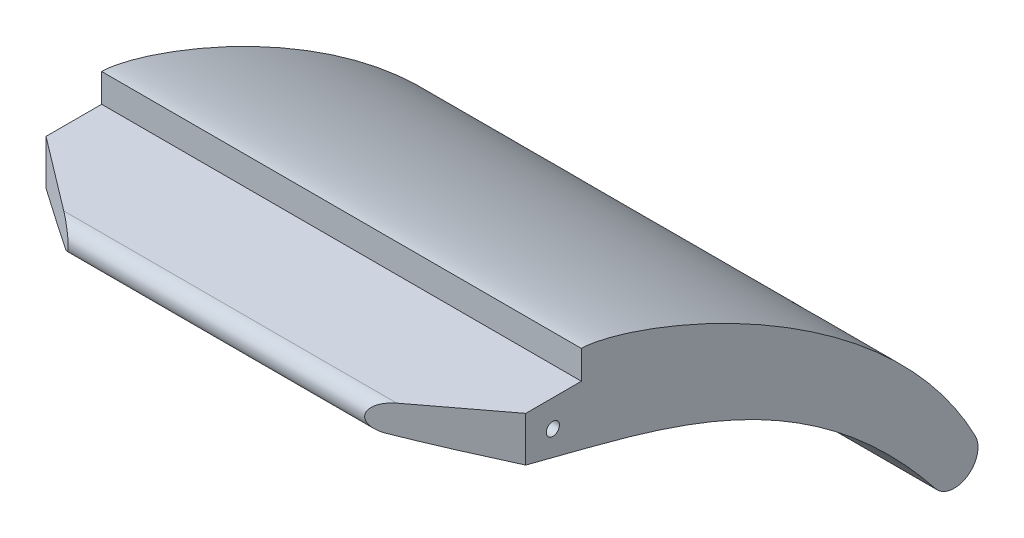
SolidWorks part; units mm, degrees
ref_plane "Front Plane" through (0, 0, 0) normal (0, 0, 1) x (1, 0, 0)
ref_plane "Top Plane" through (0, 0, 0) normal (0, 1, 0) x (1, 0, 0)
ref_plane "Right Plane" through (0, 0, 0) normal (1, 0, 0) x (0, 0, -1)
sketch "Sketch1" plane through (0, 0, 0) normal (1, 0, 0) x (0, 0, -1)
  line L0 (-14.235, 4.6355) -> (4.9116, 4.6355)
  line L1 (4.9116, 4.6355) -> (4.9116, 9.525)
  line L2 (-99.8999, 9.525) -> (-113.4123, 9.525) construction
  circle A0 centre (0, 0) radius 1.1303
  arc A1 (72.7015, -37.4179) -> (65.8572, -41.85) centre (69.0658, -39.3042) cw
  arc A2 (-14.235, 4.6355) -> (-15.0044, 0) centre (-14.235, 2.2539) ccw
  spline S0 degree 3 poles (-15.0044, 0) (9.3741, -8.3212) (39.4234, -8.5344) (65.8572, -41.85) knots 0 0 0 0 1 1 1 1
  spline S1 degree 3 poles (4.9116, 9.525) (13.3569, 9.525) (56.9145, -6.9889) (72.7015, -37.4179) knots 0 0 0 0 1 1 1 1
  point P13 (0, 0)
  dimension "D1" = 9.525
  dimension "D2" = 4.8895
extrude "Boss-Extrude1" add sketch "Sketch1" along normal blind 82.55
sketch "Sketch2" plane through (0, 4.6355, 0) normal (0, 1, 0) x (1, 0, 0)
  line L0 (0, -4.6617) -> (0, -18.4899)
  line L1 (0, 4.9116) -> (0, -14.235) construction
  line L2 (0, -18.4899) -> (18.2363, -18.4899)
  line L3 (18.2363, -18.4899) -> (0, -4.6617)
  line L4 (82.55, -4.6617) -> (82.55, -18.4899)
  line L6 (82.55, -18.4899) -> (64.3137, -18.4899)
  line L7 (64.3137, -18.4899) -> (82.55, -4.6617)
  line L8 (82.55, 4.9116) -> (82.55, -14.235) construction
extrude "Cut-Extrude1" cut sketch "Sketch2" against normal through all
